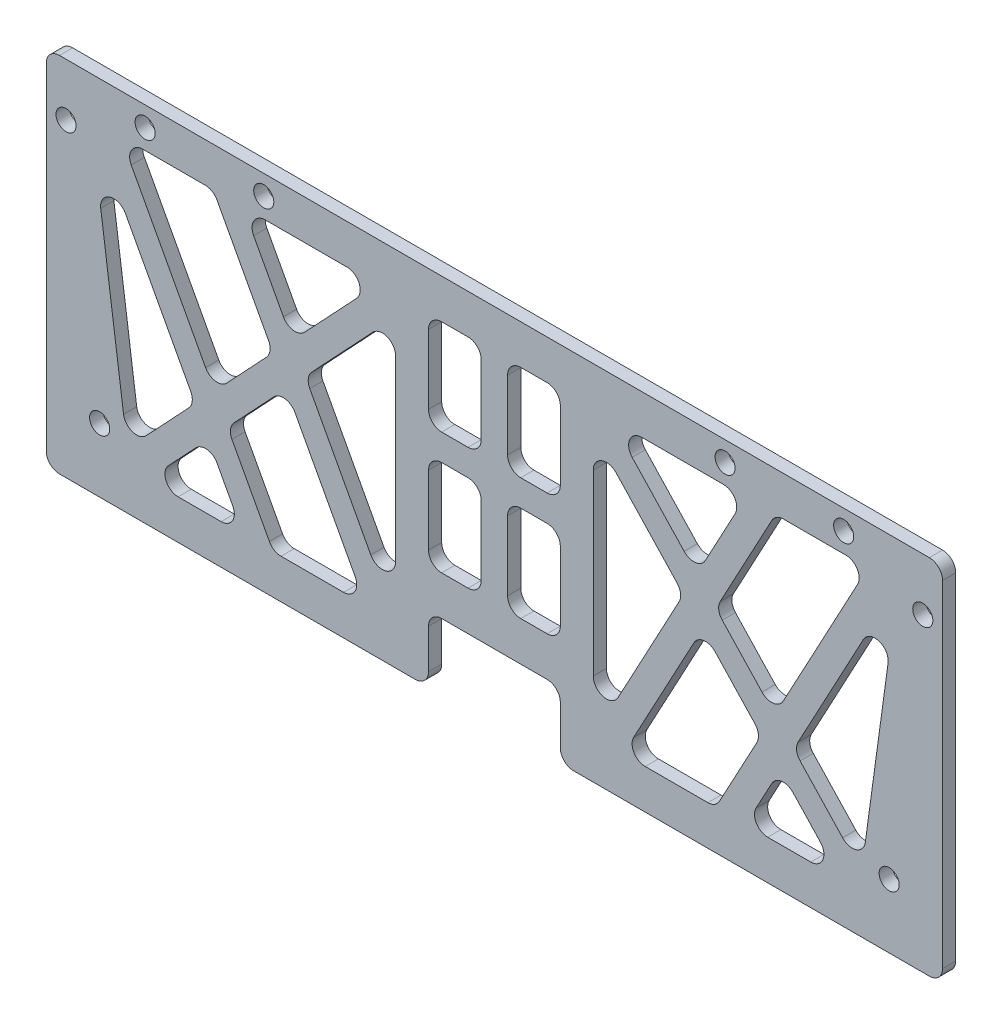
SolidWorks part; units mm, degrees
material "Thornel Mat VMA"
ref_plane "前视基准面" through (0, 0, 0) normal (0, 0, 1) x (1, 0, 0)
ref_plane "上视基准面" through (0, 0, 0) normal (0, 1, 0) x (1, 0, 0)
ref_plane "右视基准面" through (0, 0, 0) normal (1, 0, 0) x (0, 0, -1)
other "Configuration Table"
sketch "草图1" plane through (0, 0, 0) normal (0, 0, 1) x (1, 0, 0)
  line L1 (-68, -27.5) -> (68, -27.5)
  line L2 (-68, -27.5) -> (-68, 27.5)
  line L3 (-68, 27.5) -> (68, 27.5)
  line L4 (68, -27.5) -> (68, 27.5)
  line L5 (-68, -27.5) -> (68, 27.5) construction
  line L6 (-68, 27.5) -> (68, -27.5) construction
  point P0 (0, 0)
  dimension "D1" = 136
  dimension "D2" = 55
extrude "凸台-拉伸1" add sketch "草图1" along normal blind 2
sketch "草图2" plane through (0, 0, 0) normal (0, 0, -1) x (-1, 0, 0)
  line L0 (0, 0) -> (0, 35.5803) construction
  circle A0 centre (65, 19.5) radius 1.25 construction
  circle A1 centre (59.9, -17.8) radius 1.65 construction
  circle A2 centre (65, 19.5) radius 1.25 construction
  circle A3 centre (59.9, -17.8) radius 1.65 construction
  circle A4 centre (59.9, -17.8) radius 1.525
  circle A5 centre (65, 19.5) radius 1.525
  dimension "D1" = 3.05
extrude "切除-拉伸1" cut sketch "草图2" against normal blind 10
mirror "镜向1" about plane through (0, 0, 0) normal (1, 0, 0) of "切除-拉伸1"
sketch "草图3" plane through (0, 0, 0) normal (0, 0, -1) x (-1, 0, 0)
  line L0 (68, -27.5) -> (-68, -27.5) construction
  line L1 (10, -37.5) -> (-10, -37.5)
  line L2 (10, -37.5) -> (10, -17.5)
  line L3 (10, -17.5) -> (-10, -17.5)
  line L4 (-10, -37.5) -> (-10, -17.5)
  line L5 (10, -37.5) -> (-10, -17.5) construction
  line L6 (10, -17.5) -> (-10, -37.5) construction
  point P0 (0, -27.5)
  dimension "D1" = 20
  dimension "D2" = 10
extrude "切除-拉伸2" cut sketch "草图3" against normal blind 22
fillet "圆角1" radius 2 4 edges at (10, -27.5, 1) (10, -17.5, 1) (-10, -27.5, 1) (-10, -17.5, 1)
sketch "草图4" plane through (0, 0, 2) normal (0, 0, 1) x (1, 0, 0)
  line L0 (-61.2362, 21.5) -> (-55.3569, -21.5)
  line L1 (-55.3569, -21.5) -> (-15, -21.5)
  line L2 (-15, -21.5) -> (-15, 21.5)
  line L3 (-15, 21.5) -> (-61.2362, 21.5)
  line L4 (-65, 19.5) -> (-59.9, -17.8) construction
  line L5 (-10, -25.5) -> (-10, -19.5) construction
  line L6 (-68, -27.5) -> (-12, -27.5) construction
  line L7 (68, 27.5) -> (-68, 27.5) construction
  dimension "D1" = 8
  dimension "D2" = 5
  dimension "D3" = 6
  dimension "D4" = 6
extrude "切除-拉伸3" cut sketch "草图4" against normal blind 22
sketch "草图5" plane through (0, 0, 2) normal (0, 0, 1) x (1, 0, 0)
  line L0 (-61.2362, 21.5) -> (-38.1181, -21.5)
  line L1 (-55.3569, -21.5) -> (-15, -21.5) construction
  line L2 (-38.1181, 21.5) -> (-15, -21.5)
  line L3 (-15, 21.5) -> (-61.2362, 21.5) construction
  line L4 (-56.6948, 21.5) -> (-33.5767, -21.5)
  line L5 (-42.6596, 21.5) -> (-19.5414, -21.5)
  line L7 (-61.2362, 21.5) -> (-56.6948, 21.5)
  line L8 (-42.6596, 21.5) -> (-38.1181, 21.5)
  line L9 (-38.1181, -21.5) -> (-33.5767, -21.5)
  line L10 (-19.5414, -21.5) -> (-15, -21.5)
  dimension "D1" = 4
  dimension "D2" = 4
extrude "凸台-拉伸2" add sketch "草图5" against normal up to surface (2 mm away) up to face at (-36.6483, 0, 0)
mirror "镜向3" about plane through (0, 0, 0) normal (1, 0, 0) of "切除-拉伸3", "凸台-拉伸2"
sketch "草图6" plane through (0, 0, 2) normal (0, 0, 1) x (1, 0, 0)
  line L0 (0, 5) -> (0, 0) construction
  line L1 (-10, -11.5) -> (10, -11.5)
  line L2 (-10, -11.5) -> (-10, 21.5)
  line L3 (-10, 21.5) -> (10, 21.5)
  line L4 (10, -11.5) -> (10, 21.5)
  line L5 (-10, -11.5) -> (10, 21.5) construction
  line L6 (-10, 21.5) -> (10, -11.5) construction
  line L7 (15, -21.5) -> (15, 21.5) construction
  line L8 (-8, -17.5) -> (8, -17.5) construction
  line L10 (15, 21.5) -> (38.1181, 21.5) construction
  line L11 (0, 21.5) -> (0, -11.5) construction
  line L12 (-10, 5) -> (10, 5) construction
  line L13 (-10, 3) -> (10, 3)
  line L14 (-2, 21.5) -> (-2, -11.5)
  line L15 (-10, 7) -> (10, 7)
  line L16 (2, 21.5) -> (2, -11.5)
  point P0 (0, 5)
  dimension "D1" = 5
  dimension "D2" = 6
  dimension "D3" = 2
  dimension "D4" = 2
extrude "切除-拉伸4" cut sketch "草图6" against normal up to surface (2 mm away) contours L2 L15 L14 L3 | L3 L16 L15 L4 | L13 L16 L1 L4 | L14 L13 L2 L1 up to face at (38.1181, 0, 0)
sketch "草图7" plane through (0, 0, 0) normal (0, 0, -1) x (-1, 0, 0)
  line L0 (-15, 21.5) -> (-55.3569, -21.5) construction
  line L1 (-16.4583, 22.8687) -> (-56.8152, -20.1313)
  line L2 (-13.5417, 20.1313) -> (-53.8986, -22.8687)
  arc A1 (-16.4583, 22.8687) -> (-13.5417, 20.1313) centre (-15, 21.5) cw
  arc A2 (-56.8152, -20.1313) -> (-53.8986, -22.8687) centre (-55.3569, -21.5) ccw
  dimension "D1" = 2
  dimension "D2" = 2
extrude "凸台-拉伸3" add sketch "草图7" against normal up to surface (2 mm away) up to face at (22.706, 7.1667, 2)
mirror "镜向4" about plane through (0, 0, 0) normal (1, 0, 0) of "凸台-拉伸3"
fillet "圆角2" radius 2 56 edges at (-10, -11.5, 1) (-10, 3, 1) (-2, 3, 1) (-2, -11.5, 1) (-10, 7, 1) (-10, 21.5, 1) (-2, 21.5, 1) (-2, 7, 1) (2, 21.5, 1) (10, 21.5, 1) (10, 7, 1) (2, 7, 1) (2, 3, 1) (10, 3, 1) (10, -11.5, 1) (2, -11.5, 1) (61.2362, 21.5, 1) (55.7057, -18.9491, 1) (45.3956, -7.9638, 1) (42.6596, 21.5, 1) (56.6948, 21.5, 1) (42.5082, -4.8873, 1) (33.5847, 4.6206, 1) (38.1181, 21.5, 1) (30.6973, 7.6972, 1) (17.7429, 21.5, 1) (15, -21.5, 1) (15, 18.5775, 1) (28.6993, 3.9809, 1) (33.5767, -21.5, 1) (19.5414, -21.5, 1) (31.5867, 0.9044, 1) (40.5102, -8.6035, 1) (38.1181, -21.5, 1) (43.3976, -11.68, 1) (52.614, -21.5, 1) (-55.7057, -18.9491, 1) (-61.2362, 21.5, 1) (-45.3956, -7.9638, 1) (-42.5082, -4.8873, 1) (-56.6948, 21.5, 1) (-42.6596, 21.5, 1) (-33.5847, 4.6206, 1) (-30.6973, 7.6972, 1) (-38.1181, 21.5, 1) (-17.7429, 21.5, 1) (-15, 18.5775, 1) (-15, -21.5, 1) (-28.6993, 3.9809, 1) (-31.5867, 0.9044, 1) (-40.5102, -8.6035, 1) (-43.3976, -11.68, 1) (-38.1181, -21.5, 1) (-52.614, -21.5, 1) (-19.5414, -21.5, 1) (-33.5767, -21.5, 1)
fillet "圆角3" radius 2 4 edges at (-68, -27.5, 1) (68, -27.5, 1) (-68, 27.5, 1) (68, 27.5, 1)
sketch "草图8" plane through (0, 0, 0) normal (0, 0, -1) x (-1, 0, 0)
  line L0 (68, 24.5) -> (53, 24.5) construction
  line L1 (68, 25.5) -> (68, -25.5) construction
  line L2 (53, 24.5) -> (35, 24.5) construction
  line L3 (-66, 27.5) -> (66, 27.5) construction
  circle A0 centre (53, 24.5) radius 1.525
  circle A1 centre (35, 24.5) radius 1.525
  dimension "D2" = 3.05
  dimension "D1" = 3
  dimension "D3" = 15
  dimension "D4" = 18
extrude "切除-拉伸5" cut sketch "草图8" against normal blind 10
mirror "镜向5" about plane through (0, 0, 0) normal (1, 0, 0) of "切除-拉伸5"
equation "\"D4@草图4\"=\"D3@草图4\""
